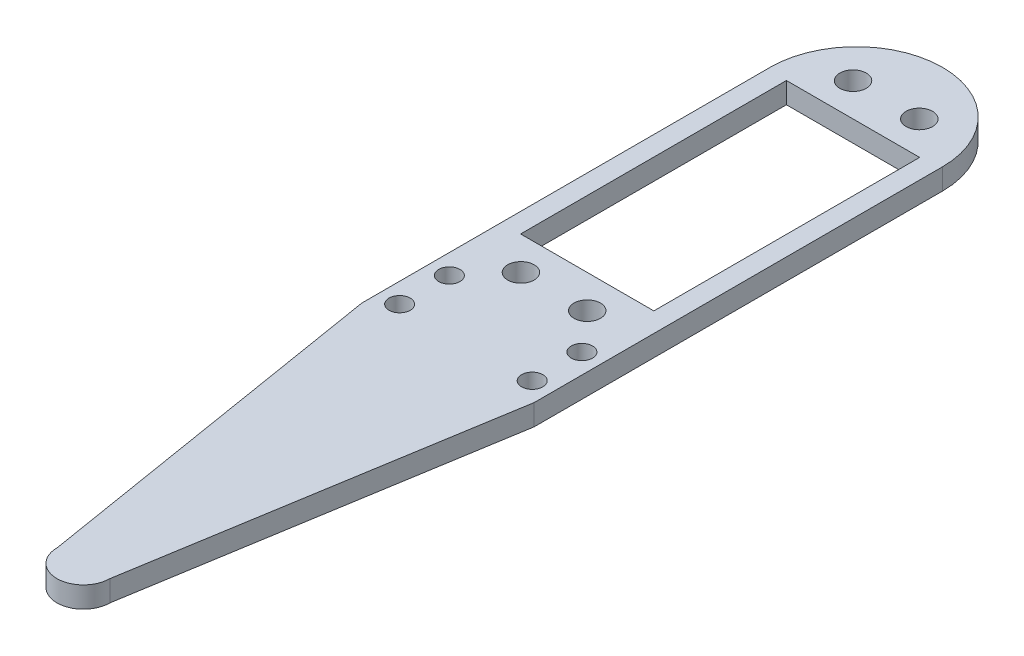
SolidWorks part; units mm, degrees
ref_plane "Front Plane" through (0, 0, 0) normal (0, 0, 1) x (1, 0, 0)
ref_plane "Top Plane" through (0, 0, 0) normal (0, 1, 0) x (1, 0, 0)
ref_plane "Right Plane" through (0, 0, 0) normal (1, 0, 0) x (0, 0, -1)
sketch "Sketch2" plane through (0, 0, 0) normal (0, 1, 0) x (1, 0, 0)
  line L0 (-13, 0) -> (-13, -61.6)
  line L1 (13, 0) -> (13, -61.6)
  line L2 (-13, -61.6) -> (-4, -116.6)
  line L3 (13, -61.6) -> (4, -116.6)
  line L4 (0, 13) -> (0, -120.6) construction
  line L5 (-4, -116.6) -> (4, -116.6) construction
  line L6 (-10.05, -0.5) -> (10.05, -0.5)
  line L7 (-10.05, -0.5) -> (-10.05, -40.6)
  line L8 (-10.05, -40.6) -> (10.05, -40.6)
  line L9 (10.05, -0.5) -> (10.05, -40.6)
  line L10 (-10.05, -0.5) -> (10.05, -40.6) construction
  line L11 (-10.05, -40.6) -> (10.05, -0.5) construction
  arc A0 (13, 0) -> (-13, 0) centre (0, 0) ccw
  arc A1 (-4, -116.6) -> (4, -116.6) centre (0, -116.6) ccw
  circle A2 centre (-5, 4.5) radius 2
  circle A4 centre (-5, -45.6) radius 2
  circle A5 centre (5, -45.6) radius 2
  circle A6 centre (5, 4.5) radius 2
  point P15 (0, -20.55)
  dimension "D1" = 4
  dimension "D8" = 13
  dimension "D10" = 4
  dimension "D2" = 50.1
  dimension "D3" = 5
  dimension "D4" = 4.5
  dimension "D5" = 40.1
  dimension "D6" = 20.1
  dimension "D7" = 5
  dimension "D9" = 55
  dimension "D11" = 16
extrude "Boss-Extrude1" add sketch "Sketch2" along normal blind 3.175
sketch "Sketch3" plane through (0, 3.175, 0) normal (0, 1, 0) x (1, 0, 0)
  circle A0 centre (10, -58.9) radius 1.6 construction
  circle A1 centre (10, -51.4) radius 1.6 construction
  circle A2 centre (-10, -58.9) radius 1.6 construction
  circle A3 centre (-10, -51.4) radius 1.6 construction
  circle A4 centre (10, -58.9) radius 1.6
  circle A5 centre (10, -51.4) radius 1.6
  circle A6 centre (-10, -58.9) radius 1.6
  circle A7 centre (-10, -51.4) radius 1.6
extrude "Cut-Extrude1" cut sketch "Sketch3" against normal through all both and the other way through all
